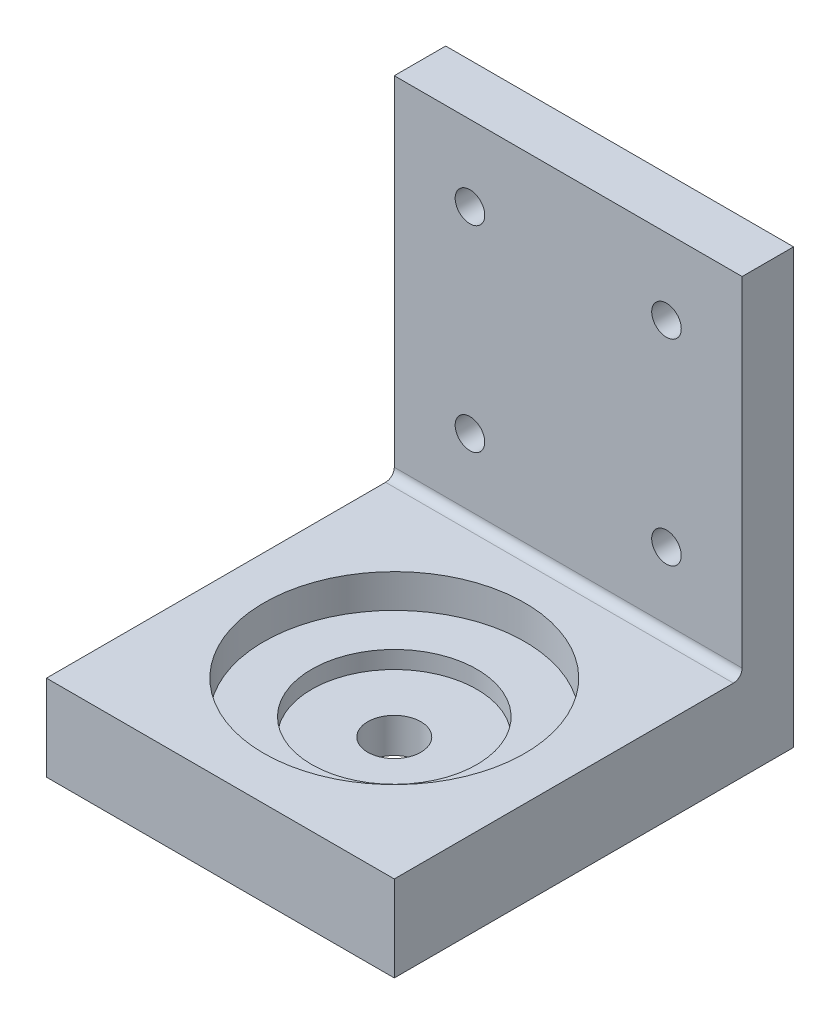
SolidWorks part; units mm, degrees
ref_plane "Front Plane" through (0, 0, 0) normal (0, 0, 1) x (1, 0, 0)
ref_plane "Top Plane" through (0, 0, 0) normal (0, 1, 0) x (1, 0, 0)
ref_plane "Right Plane" through (0, 0, 0) normal (1, 0, 0) x (0, 0, -1)
sketch "Sketch1" plane through (0, 0, 0) normal (0, 1, 0) x (1, 0, 0)
  line L1 (0, 0) -> (40, 0)
  line L2 (0, 0) -> (0, -40)
  line L3 (0, -40) -> (40, -40)
  line L4 (40, 0) -> (40, -40)
  dimension "D1" = 40
  dimension "D2" = 40
extrude "Boss-Extrude1" add sketch "Sketch1" along normal blind 9.8648
sketch "Sketch2" plane through (0, 9.8648, 0) normal (0, 1, 0) x (1, 0, 0)
  line L0 (0, 0) -> (0, -40) construction
  line L1 (0, -40) -> (40, -40) construction
  circle A0 centre (20, -20) radius 15
  point P5 (0, -20)
  point P8 (20, -40)
  dimension "D1" = 30
extrude "Cut-Extrude1" cut sketch "Sketch2" against normal blind 3.86
sketch "Sketch3" plane through (0, 6.0048, 0) normal (0, 1, 0) x (1, 0, 0)
  line L0 (0, 0) -> (0, -40) construction
  line L1 (0, -40) -> (40, -40) construction
  circle A0 centre (20, -20) radius 9.5
  point P4 (0, -20)
  point P7 (20, -40)
  dimension "D1" = 19
extrude "Cut-Extrude2" cut sketch "Sketch3" against normal blind 2
sketch "Sketch4" plane through (0, 4.0048, 0) normal (0, 1, 0) x (1, 0, 0)
  line L0 (0, 0) -> (0, -40) construction
  line L1 (0, -40) -> (40, -40) construction
  circle A0 centre (20, -20) radius 3.05
  point P4 (0, -20)
  point P7 (20, -40)
  dimension "D1" = 6.1
extrude "Cut-Extrude3" cut sketch "Sketch4" against normal through all
sketch "Sketch5" plane through (0, 0, 0) normal (0, 1, 0) x (1, 0, 0)
  line L1 (0, 0) -> (40, 0)
  line L2 (0, 0) -> (0, 5.9135)
  line L3 (0, 5.9135) -> (40, 5.9135)
  line L4 (40, 0) -> (40, 5.9135)
  dimension "D2" = 40
  dimension "D1" = 5.9135
extrude "Boss-Extrude3" add sketch "Sketch5" along normal blind 49.86
sketch "Sketch6" plane through (0, 0, 0) normal (0, 0, 1) x (1, 0, 0)
  line L8 (0, 9.8648) -> (40, 9.8648)
  line L9 (40, 9.8648) -> (40, 49.86)
  line L10 (40, 49.86) -> (0, 49.86)
  line L11 (0, 49.86) -> (0, 9.8648)
  line L12 (0, 9.8648) -> (40, 9.8648)
  line L13 (40, 9.8648) -> (40, 49.86)
  line L14 (40, 49.86) -> (0, 49.86)
  line L15 (0, 49.86) -> (0, 9.8648)
  dimension "D1" = 0
sketch "Sketch7" plane through (0, 0, 0) normal (0, 0, 1) x (1, 0, 0)
  line L0 (0, 9.8648) -> (40, 9.8648) construction
  line L1 (0, 49.86) -> (0, 9.8648) construction
  line L2 (40, 49.86) -> (0, 49.86) construction
  line L3 (40, 9.8648) -> (40, 49.86) construction
  circle A0 centre (8.7, 18.5648) radius 1.7
  circle A1 centre (31.3, 18.5648) radius 1.7
  circle A2 centre (31.3, 41.16) radius 1.7
  circle A3 centre (8.7, 41.16) radius 1.7
  dimension "D1" = 3.4
  dimension "D2" = 8.7
  dimension "D4" = 8.7
  dimension "D5" = 8.7
  dimension "D3" = 8.7
extrude "Cut-Extrude4" cut sketch "Sketch7" against normal through all
fillet "Fillet2" radius 1 1 edges at (20, 9.8648, 0)
equation "\"P\"= 300"
equation "\"l\"= 12"
equation "\"E\"= 3 * 10 ^ 9"
equation "\"stress\"= 20 * 10 ^ 6"
equation "\"defl\"= .3"
equation "\"b\"= 40"
equation "\"L1\"= 40"
equation "\"M\"= \"P\" * \"l\""
equation "\"h1defl\"= ( ( \"M\" * ( \"L1\" ^ 2 ) * 6 ) / ( \"E\" * \"b\" * \"defl\" ) ) ^ ( 1 / 3 ) * 100"
equation "\"D1@Sketch1\"=\"b\""
equation "\"D2@Sketch1\"=\"L1\""
equation "\"D1@Boss-Extrude1\"=\"h1defl\""
equation "\"D2@Sketch5\"=\"b\""
equation "\"h2defl\"= ( ( \"M\" * ( \"L2\" ^ 2 ) * 6 ) / ( \"E\" * \"b\" * \"defl\" ) ) ^ ( 1 / 3 ) * 100"
equation "\"L2\"= \"h1defl\" + 1.7 + 7"
equation "\"D1@Sketch5\"=\"h2defl\""
